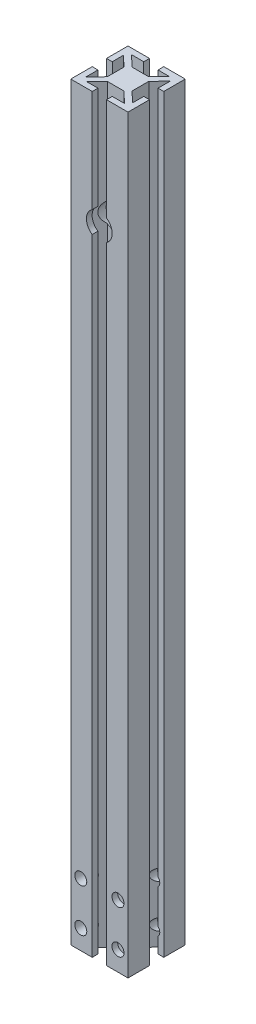
SolidWorks part; units mm, degrees
material "1060 Alloy"
ref_plane "Front Plane" through (0, 0, 0) normal (0, 0, 1) x (1, 0, 0)
ref_plane "Top Plane" through (0, 0, 0) normal (0, 1, 0) x (1, 0, 0)
ref_plane "Right Plane" through (0, 0, 0) normal (1, 0, 0) x (0, 0, -1)
sketch "Sketch1" plane through (0, 0, 0) normal (0, 1, 0) x (1, 0, 0)
  line L1 (-10, 10) -> (10, 10) construction
  line L2 (-10, 10) -> (-10, -10) construction
  line L3 (-10, -10) -> (10, -10) construction
  line L4 (10, 10) -> (10, -10) construction
  line L5 (-10, 10) -> (10, -10) construction
  line L6 (-10, -10) -> (10, 10) construction
  circle A0 centre (0, 0) radius 2
  point P0 (0, 0)
  dimension "D3" = 4
  dimension "D1" = 20
  dimension "D2" = 20
sketch "Sketch2" plane through (0, 0, 0) normal (0, 1, 0) x (1, 0, 0)
  line L0 (-10, 2.5) -> (-10, -2.5) construction
  line L1 (-10, 10) -> (-10, -10) construction
  line L2 (-10, -10) -> (-10, -2.5)
  line L3 (-10, -2.5) -> (-8, -2.5)
  line L4 (-8, -2.5) -> (-8, -6.7683)
  line L5 (-8, -6.7683) -> (-4.3583, -2.9445)
  line L6 (-4.3583, -2.9445) -> (-2.91, -4.3238)
  line L7 (-2.91, -4.3238) -> (-6.4243, -8)
  line L8 (-6.4243, -8) -> (-2.5, -8)
  line L9 (-2.5, -8) -> (-2.5, -10)
  line L10 (-10, -10) -> (10, -10) construction
  line L11 (-2.5, -10) -> (-10, -10)
  line L12 (-2.5, -10) -> (2.5, -10) construction
  line L14 (-10, -10) -> (10, 10) construction
  line L15 (-10, 2.5) -> (-10, 10)
  line L16 (-10, 10) -> (-2.5, 10)
  line L17 (-2.5, 10) -> (-2.5, 8)
  line L18 (-2.5, 8) -> (-6.7683, 8)
  line L19 (-6.7683, 8) -> (-2.9445, 4.3583)
  line L20 (-2.9445, 4.3583) -> (-4.3238, 2.91)
  line L21 (-4.3238, 2.91) -> (-8, 6.4243)
  line L22 (-8, 6.4243) -> (-8, 2.5)
  line L23 (-8, 2.5) -> (-10, 2.5)
  line L24 (2.5, 10) -> (10, 10)
  line L25 (10, 10) -> (10, 2.5)
  line L26 (10, 2.5) -> (8, 2.5)
  line L27 (8, 2.5) -> (8, 6.7683)
  line L28 (8, 6.7683) -> (4.3583, 2.9445)
  line L29 (4.3583, 2.9445) -> (2.91, 4.3238)
  line L30 (2.91, 4.3238) -> (6.4243, 8)
  line L31 (6.4243, 8) -> (2.5, 8)
  line L32 (2.5, 8) -> (2.5, 10)
  line L33 (10, -2.5) -> (10, -10)
  line L34 (10, -10) -> (2.5, -10)
  line L35 (2.5, -10) -> (2.5, -8)
  line L36 (2.5, -8) -> (6.7683, -8)
  line L37 (6.7683, -8) -> (2.9445, -4.3583)
  line L38 (2.9445, -4.3583) -> (4.3238, -2.91)
  line L39 (4.3238, -2.91) -> (8, -6.4243)
  line L40 (8, -6.4243) -> (8, -2.5)
  line L41 (8, -2.5) -> (10, -2.5)
  line L42 (-10, 10) -> (10, -10) construction
  line L43 (-4.3238, 4.3238) -> (4.3238, 4.3238)
  line L44 (-4.3238, 4.3238) -> (-4.3238, -4.3238)
  line L45 (-4.3238, -4.3238) -> (4.3238, -4.3238)
  line L46 (4.3238, 4.3238) -> (4.3238, -4.3238)
  line L47 (-4.3238, 4.3238) -> (4.3238, -4.3238) construction
  line L48 (-4.3238, -4.3238) -> (4.3238, 4.3238) construction
  point P5 (-10, 0)
  point P11 (0, 0)
  point P14 (-3.6341, -3.6341)
  point P19 (0, -10)
  dimension "D1" = 5
  dimension "D2" = 5
  dimension "D3" = 2
  dimension "D4" = 2
  dimension "D5" = 2
  dimension "D6" = 2
  dimension "D7" = 9
  dimension "D8" = 4
extrude "Boss-Extrude1" add sketch "Sketch2" along normal blind 262 contours L45 L44 L6 L5 L4 L3 L2 L11 L9 L8 L7 | L46 L29 L43 L20 L44 L6 L45 L38 | L39 L46 L45 L38 L37 L36 L35 L34 L33 L41 L40 | L43 L46 L29 L28 L27 L26 L25 L24 L32 L31 L30 | L44 L43 L20 L19 L18 L17 L16 L15 L23 L22 L21 | L46 L38 L45 | L46 L43 L29
sketch "Sketch4" plane through (10, 0, 0) normal (1, 0, 0) x (0, 0, -1)
  line L0 (0.0337, 262) -> (0.0337, 210.6) construction
  line L1 (2.9773, 262) -> (-2.91, 262) construction
  line L2 (0.0337, 210.6) -> (0.0337, 197.6) construction
  line L3 (0.0337, 197.6) -> (0.0337, 177.6) construction
  circle A0 centre (0.0337, 210.6) radius 2
  circle A1 centre (0.0337, 197.6) radius 2
  circle A2 centre (0.0337, 177.6) radius 2
  dimension "D2" = 4
  dimension "D5" = 4
  dimension "D6" = 4
  dimension "D1" = 51.4
  dimension "D3" = 13
  dimension "D4" = 20
extrude "Cut-Extrude1" cut sketch "Sketch4" against normal blind 110 contours A1 | A2 | A0
sketch "Sketch5" plane through (0, 0, -10) normal (0, 0, -1) x (-1, 0, 0)
  line L0 (0.0337, 262) -> (0.0337, 222.49) construction
  line L1 (2.9773, 262) -> (-2.91, 262) construction
  circle A0 centre (0.0337, 222.49) radius 4.5
  dimension "D2" = 9
  dimension "D1" = 39.51
extrude "Cut-Extrude2" cut sketch "Sketch5" against normal blind 110 contours A0
sketch "Sketch7" plane through (0, 0, -10) normal (0, 0, -1) x (-1, 0, 0)
  line L0 (0, 0) -> (0, 28) construction
  line L1 (6.5, 21.8611) -> (-6.5, 21.8611) construction
  line L2 (6.5, 6.8611) -> (-6.5, 6.8611) construction
  line L3 (-6.5, 6.8611) -> (-6.5, 21.8611) construction
  line L4 (6.5, 21.8611) -> (6.5, 6.8611) construction
  line L5 (10, 262) -> (10, 0) construction
  circle A0 centre (6.5, 21.8611) radius 2.1
  circle A1 centre (6.5, 6.8611) radius 2.1
  circle A2 centre (-6.5, 21.8611) radius 2.1
  circle A3 centre (-6.5, 6.8611) radius 2.1
  point P6 (0, 21.8611)
  point P9 (0, 6.8611)
  dimension "D3" = 4.2
  dimension "D4" = 4.2
  dimension "D1" = 28
  dimension "D2" = 3.5
  dimension "D5" = 15
sketch "Sketch9" plane through (-10, 0, 0) normal (-1, 0, 0) x (0, 0, 1)
  line L0 (0, 0) -> (0, 28) construction
  line L1 (6.5, 6) -> (-6.5, 6) construction
  line L2 (-6.5, 6) -> (-6.5, 21) construction
  line L3 (-6.5, 21) -> (6.5, 21) construction
  line L4 (6.5, 21) -> (6.5, 6) construction
  line L5 (10, 262) -> (10, 0) construction
  line L6 (-10, 0) -> (10, 0) construction
  circle A0 centre (6.5, 6) radius 2.1
  circle A1 centre (6.5, 21) radius 2.1
  circle A2 centre (-6.5, 21) radius 2.1
  circle A3 centre (-6.5, 6) radius 2.1
  point P6 (0, 6)
  dimension "D2" = 4.2
  dimension "D1" = 28
  dimension "D3" = 15
  dimension "D4" = 3.5
  dimension "D5" = 6
extrude "Cut-Extrude5" cut sketch "Sketch7" against normal blind 50
